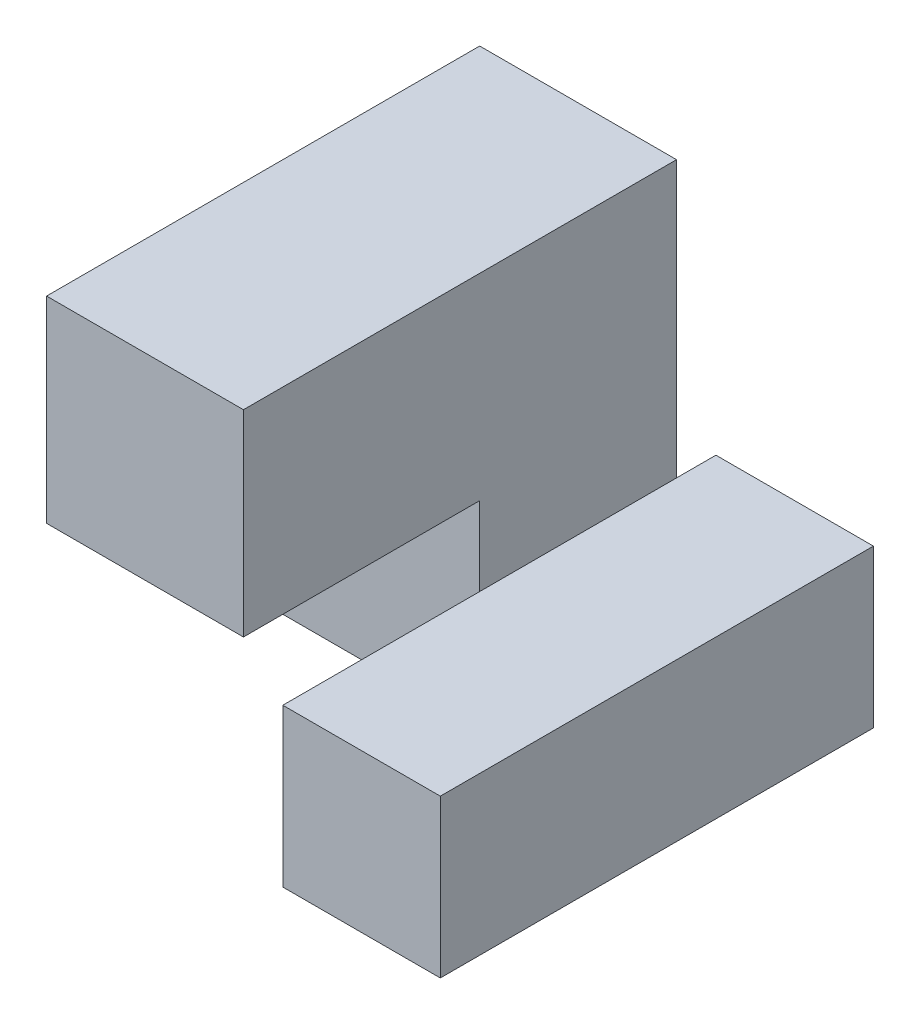
SolidWorks part; units mm, degrees
ref_plane "Front Plane" through (0, 0, 0) normal (0, 0, 1) x (1, 0, 0)
ref_plane "Top Plane" through (0, 0, 0) normal (0, 1, 0) x (1, 0, 0)
ref_plane "Right Plane" through (0, 0, 0) normal (1, 0, 0) x (0, 0, -1)
sketch "Sketch1" plane through (0, 0, 0) normal (0, 0, 1) x (1, 0, 0)
  line L1 (0, 0) -> (10, 0)
  line L2 (0, 0) -> (0, 20)
  line L3 (0, 20) -> (10, 20)
  line L4 (10, 0) -> (10, 20)
extrude "Boss-Extrude1" add sketch "Sketch1" along normal blind 10
sketch "Sketch2" plane through (0, 0, 0) normal (0, 0, 1) x (1, 0, 0)
  line L0 (0, 20) -> (0, 0) construction
  line L1 (0, 10) -> (10, 10)
  line L2 (0, 10) -> (0, 20)
  line L3 (0, 20) -> (10, 20)
  line L4 (10, 10) -> (10, 20)
extrude "Boss-Extrude2" add sketch "Sketch2" along normal blind 22
sketch "Sketch3" plane through (0, 0, 0) normal (0, 0, 1) x (1, 0, 0)
  line L1 (12, 0) -> (20, 0)
  line L2 (12, 0) -> (12, 8)
  line L3 (12, 8) -> (20, 8)
  line L4 (20, 0) -> (20, 8)
extrude "Boss-Extrude3" add sketch "Sketch3" along normal up to vertex (22 mm away) separate body up to point (10, 10, 22)
